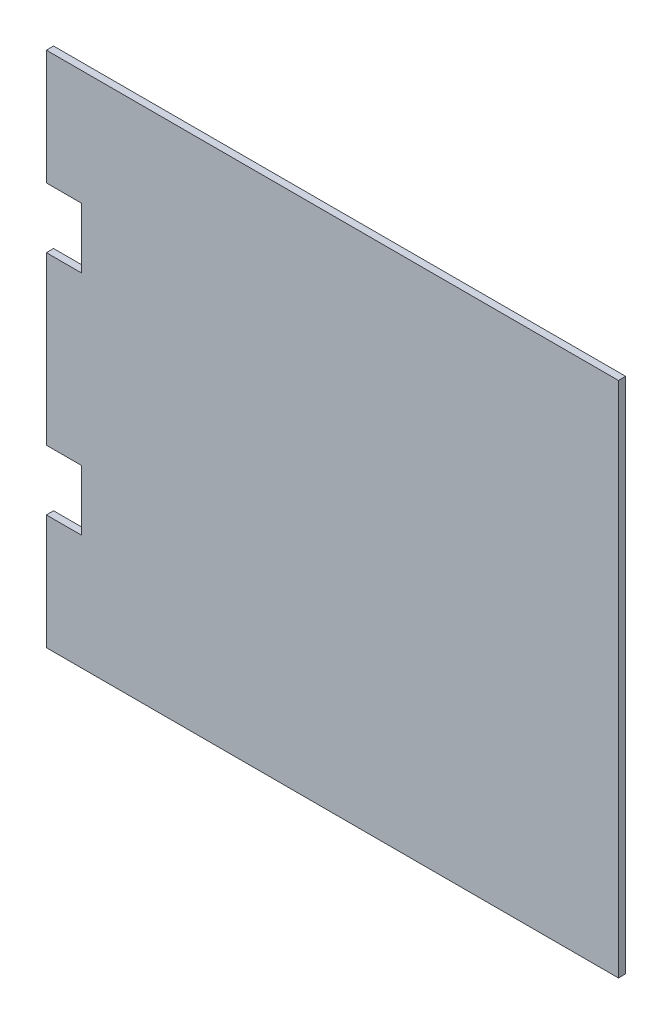
SolidWorks part; units mm, degrees
ref_plane "Plan de face" through (0, 0, 0) normal (0, 0, 1) x (1, 0, 0)
ref_plane "Plan de dessus" through (0, 0, 0) normal (0, 1, 0) x (1, 0, 0)
ref_plane "Plan de droite" through (0, 0, 0) normal (1, 0, 0) x (0, 0, -1)
sketch "Esquisse1" plane through (0, 0, 0) normal (0, 0, 1) x (1, 0, 0)
  line L1 (-200, 180) -> (200, 180)
  line L2 (-200, 180) -> (-200, -180)
  line L3 (-200, -180) -> (200, -180)
  line L4 (200, 180) -> (200, -180)
  line L5 (-200, 180) -> (200, -180) construction
  line L6 (-200, -180) -> (200, 180) construction
  point P0 (0, 0)
  dimension "D1" = 400
  dimension "D2" = 360
extrude "Boss.-Extru.1" add sketch "Esquisse1" along normal blind 5
sketch "Esquisse2" plane through (0, 0, 5) normal (0, 0, 1) x (1, 0, 0)
  line L0 (-200, 180) -> (-200, -180) construction
  line L1 (-173.5604, 100) -> (-200, 100)
  line L2 (-173.5604, 100) -> (-173.5604, 58)
  line L3 (-173.5604, 58) -> (-200, 58)
  line L4 (-200, 100) -> (-200, 58)
  line L5 (-173.5604, 100) -> (-200, 58) construction
  line L6 (-173.5604, 58) -> (-200, 100) construction
  line L7 (200, 180) -> (-200, 180) construction
  line L8 (-250.1404, 0) -> (-138.2776, 0) construction
  line L9 (-173.5604, -58) -> (-200, -58)
  line L10 (-200, -100) -> (-200, -58)
  line L11 (-173.5604, -100) -> (-200, -100)
  line L12 (-173.5604, -100) -> (-173.5604, -58)
  point P0 (-186.7802, 79)
  dimension "D1" = 42
  dimension "D2" = 122
extrude "Enlèv. mat.-Extru.1" cut sketch "Esquisse2" against normal blind 5 contours L2 L1 L4 L3 | L9 L10 L11 L12
sketch "Esquisse3" plane through (-200, 0, 0) normal (-1, 0, 0) x (0, 0, 1)
  line L4 (5, 58) -> (0, 58)
  line L5 (0, 58) -> (0, -58)
  line L6 (0, -58) -> (5, -58)
  line L7 (5, -58) -> (5, 58)
  line L8 (5, 58) -> (0, 58)
  line L9 (0, 58) -> (0, -58)
  line L10 (0, -58) -> (5, -58)
  line L11 (5, -58) -> (5, 58)
  line L12 (0, 180) -> (0, 100)
  line L13 (0, 100) -> (5, 100)
  line L14 (5, 100) -> (5, 180)
  line L15 (5, 180) -> (0, 180)
  line L16 (0, 180) -> (0, 100)
  line L17 (0, 100) -> (5, 100)
  line L18 (5, 100) -> (5, 180)
  line L19 (5, 180) -> (0, 180)
  line L20 (5, -100) -> (0, -100)
  line L21 (0, -100) -> (0, -180)
  line L22 (0, -180) -> (5, -180)
  line L23 (5, -180) -> (5, -100)
  line L24 (5, -100) -> (0, -100)
  line L25 (0, -100) -> (0, -180)
  line L26 (0, -180) -> (5, -180)
  line L27 (5, -180) -> (5, -100)
  dimension "D1" = 0
  dimension "D2" = 0
  dimension "D3" = 0
extrude "Enlèv. mat.-Extru.2" cut sketch "Esquisse3" against normal blind 2
